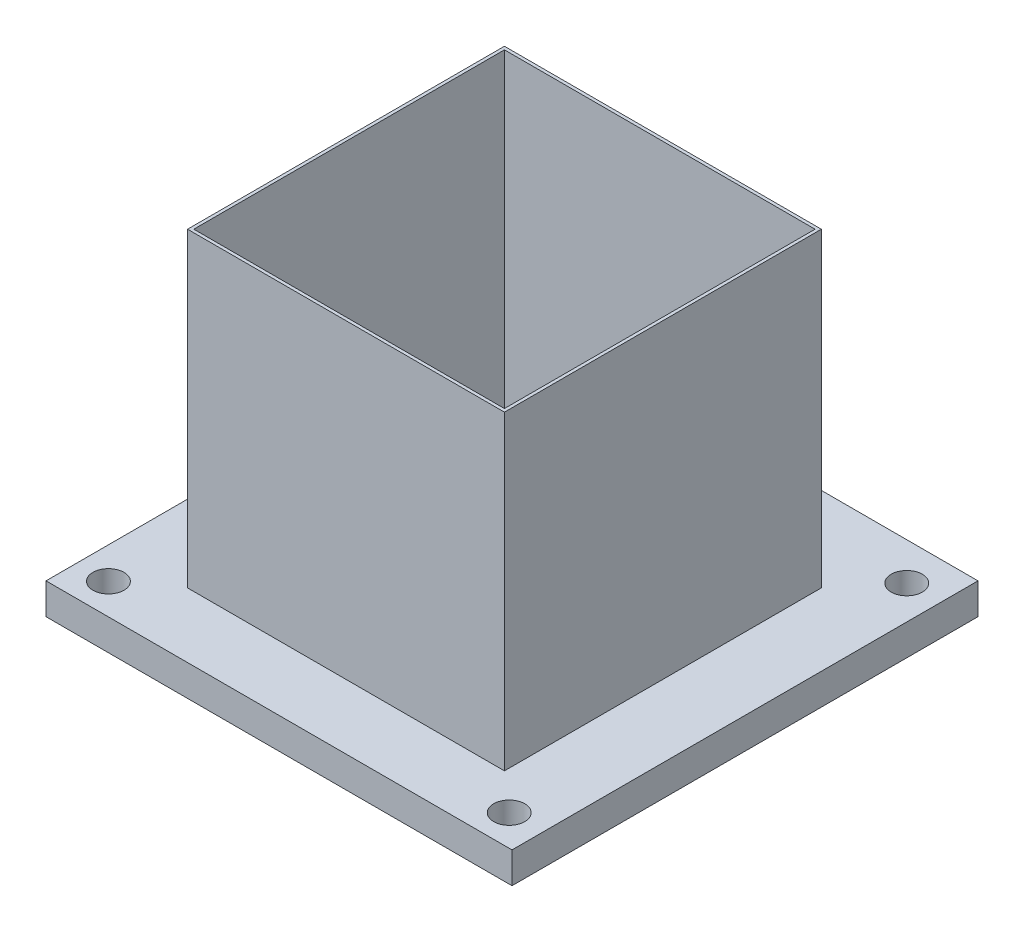
SolidWorks part; units mm, degrees
ref_plane "Front Plane" through (0, 0, 0) normal (0, 0, 1) x (1, 0, 0)
ref_plane "Top Plane" through (0, 0, 0) normal (0, 1, 0) x (1, 0, 0)
ref_plane "Right Plane" through (0, 0, 0) normal (1, 0, 0) x (0, 0, -1)
sketch "Sketch1" plane through (0, 0, 0) normal (0, 1, 0) x (1, 0, 0)
  line L1 (0, 0) -> (38.1, 0)
  line L2 (0, 0) -> (0, 38.1)
  line L3 (0, 38.1) -> (38.1, 38.1)
  line L4 (38.1, 0) -> (38.1, 38.1)
  line L5 (6.5418, 30.9395) -> (31.9418, 30.9395)
  line L6 (6.5418, 30.9395) -> (6.5418, 5.5395)
  line L7 (6.5418, 5.5395) -> (31.9418, 5.5395)
  line L8 (31.9418, 30.9395) -> (31.9418, 5.5395)
  circle A0 centre (2.5847, 35.023) radius 1.27
  circle A1 centre (35.351, 35.023) radius 1.27
  circle A3 centre (2.5847, 2.5204) radius 1.27
  circle A4 centre (35.351, 2.5204) radius 1.27
  dimension "D7" = 2.54
  dimension "D4" = 2.54
  dimension "D1" = 38.1
  dimension "D2" = 38.1
  dimension "D3" = 25.4
  dimension "D5" = 25.4
extrude "Boss-Extrude2" add sketch "Sketch1" along normal blind 2.54
sketch "Sketch3" plane through (0, 2.54, 0) normal (0, 1, 0) x (1, 0, 0)
  line L0 (31.9418, 30.9395) -> (6.5418, 30.9395) construction
  line L1 (6.5418, 30.9395) -> (31.9418, 30.9395)
  line L2 (6.5418, 30.9395) -> (6.5418, 5.5395)
  line L3 (6.5418, 5.5395) -> (31.9418, 5.5395)
  line L4 (31.9418, 30.9395) -> (31.9418, 5.5395)
  line L5 (6.5418, 30.9395) -> (6.5418, 5.5395) construction
  line L6 (6.5418, 5.5395) -> (31.9418, 5.5395) construction
  line L7 (31.9418, 5.5395) -> (31.9418, 30.9395) construction
  line L9 (6.2878, 31.1935) -> (32.1958, 31.1935)
  line L10 (6.2878, 31.1935) -> (6.2878, 5.2855)
  line L11 (6.2878, 5.2855) -> (32.1958, 5.2855)
  line L12 (32.1958, 31.1935) -> (32.1958, 5.2855)
  point P16 (5.0577, 4.3917)
  dimension "D1" = 0.254
  dimension "D2" = 0.254
  dimension "D3" = 0.254
  dimension "D4" = 25.908
extrude "Boss-Extrude4" add sketch "Sketch3" along normal blind 25.4
